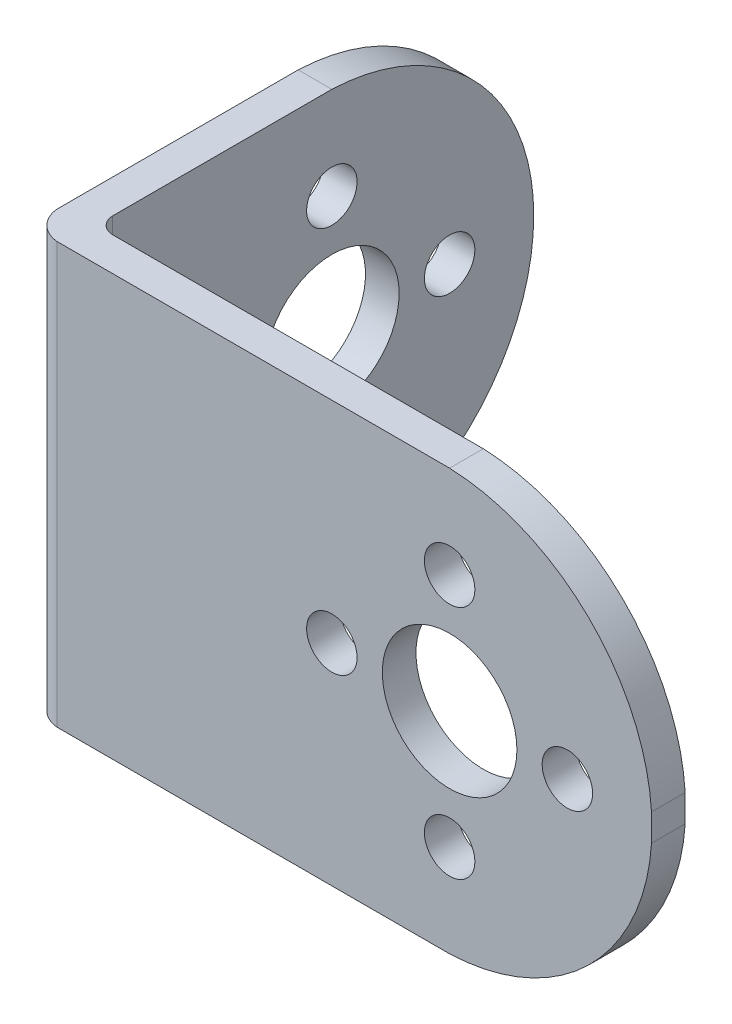
SolidWorks part; units mm, degrees
material "1060 Alloy"
ref_plane "Front Plane" through (0, 0, 0) normal (0, 0, 1) x (1, 0, 0)
ref_plane "Top Plane" through (0, 0, 0) normal (0, 1, 0) x (1, 0, 0)
ref_plane "Right Plane" through (0, 0, 0) normal (1, 0, 0) x (0, 0, -1)
sketch "Sketch1" plane through (0, 0, 0) normal (0, 1, 0) x (1, 0, 0)
  line L0 (1.6591, 0) -> (37, 0)
  line L1 (37, 0) -> (37, 2)
  line L2 (37, 2) -> (2.9676, 2)
  line L3 (0, 2) -> (0, 1.6591)
  line L4 (0, 1.6591) -> (0, 28)
  line L5 (0, 28) -> (2, 28)
  line L6 (2, 28) -> (2, 2.9676)
  arc A0 (0, 2) -> (2, 0) centre (1.8295, 1.8295) ccw
  arc A1 (2, 2.9676) -> (3.0387, 2) centre (3.0031, 3.0031) ccw
  dimension "D1" = 2
extrude "Boss-Extrude1" add sketch "Sketch1" along normal blind 25 contours A1 L6 L5 L4 L3 A0 L0 L1 L2
sketch "Sketch2" plane through (0, 0, 0) normal (-1, 0, 0) x (0, 0, 1)
  line L0 (-28, 12.5) -> (-16, 12.5) construction
  line L1 (-28, 25) -> (-28, 0) construction
  line L2 (-1.6591, 0) -> (-28, 0) construction
  line L3 (-1.6591, 25) -> (-28, 25) construction
  line L4 (-16, 25) -> (-28, 25)
  line L5 (-28, 25) -> (-28, 12.5)
  line L6 (-28, 12.5) -> (-28, 0)
  line L7 (-28, 0) -> (-16, 0)
  arc A0 (-16, 0) -> (-16, 25) centre (-15.4896, 12.5) cw
  line M3 (-28, 0) -> (-1.6591, 0)
  line M5 (-1.6591, 25) -> (-28, 25)
  line M6 (-28, 25) -> (-28, 0)
  dimension "D1" = 12
extrude "Cut-Extrude1" cut sketch "Sketch2" against normal blind 25 contours A0 M6 M5 | A0 M3 M6
sketch "Sketch4" plane through (0, 0, 0) normal (0, 0, 1) x (1, 0, 0)
  line L0 (37, 12.5) -> (25, 12.5) construction
  line L1 (37, 25) -> (37, 0) construction
  line L2 (1.6591, 0) -> (37, 0) construction
  line L3 (1.6591, 25) -> (37, 25) construction
  line L4 (25, 25) -> (37, 25)
  line L5 (37, 25) -> (37, 12.5)
  line L6 (37, 12.5) -> (37, 0)
  line L7 (37, 0) -> (25, 0)
  line L8 (25, 12.5) -> (25, 19.5) construction
  circle A0 centre (25, 12.5) radius 4
  arc A1 (25, 0) -> (25, 25) centre (24.5166, 12.5) ccw
  circle A2 centre (25, 19.5) radius 1.5
  circle A3 centre (32, 12.5) radius 1.5
  circle A4 centre (25, 5.5) radius 1.5
  circle A5 centre (18, 12.5) radius 1.5
  point P27 (25, 12.5)
  line M1 (1.6591, 0) -> (37, 0)
  line M2 (37, 0) -> (37, 25)
  line M3 (37, 25) -> (1.6591, 25)
  dimension "D1" = 3
  dimension "D2" = 4
extrude "Cut-Extrude2" cut sketch "Sketch4" against normal blind 25 contours A1 L5 M3 | A1 M1 M2
sketch "Sketch5" plane through (0, 0, 0) normal (0, 0, 1) x (1, 0, 0)
  line L0 (37, 12.5) -> (25, 12.5) construction
  line L1 (37, 13.3055) -> (37, 11.6945) construction
  line L2 (25, 12.5) -> (25, 19.5) construction
  circle A0 centre (25, 12.5) radius 4
  circle A5 centre (25, 19.5) radius 1.5
  circle A6 centre (32, 12.5) radius 1.5
  circle A7 centre (25, 5.5) radius 1.5
  circle A8 centre (18, 12.5) radius 1.5
  point P16 (25, 12.5)
  point P17 (25, 12.5)
  dimension "D1" = 7
  dimension "D2" = 4
extrude "Cut-Extrude3" cut sketch "Sketch5" against normal blind 25
sketch "Sketch6" plane through (0, 0, 0) normal (-1, 0, 0) x (0, 0, 1)
  line L0 (-28, 12.5) -> (-16, 12.5) construction
  line L1 (-16, 12.5) -> (-16, 5.5) construction
  arc A0 (-16, 25) -> (-16, 0) centre (-15.4896, 12.5) ccw construction
  circle A1 centre (-16, 12.5) radius 4
  circle A2 centre (-16, 5.5) radius 1.5
  circle A3 centre (-23, 12.5) radius 1.5
  circle A4 centre (-16, 19.5) radius 1.5
  circle A5 centre (-9, 12.5) radius 1.5
  point P18 (-16, 12.5)
  dimension "D1" = 7
  dimension "D2" = 4
extrude "Cut-Extrude4" cut sketch "Sketch6" against normal blind 25
